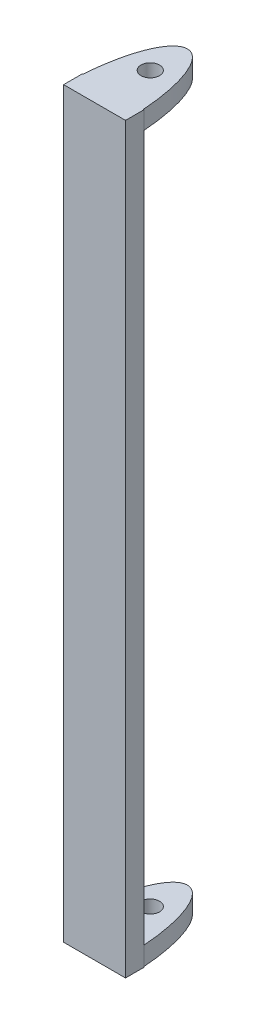
SolidWorks part; units mm, degrees
ref_plane "Front Plane" through (0, 0, 0) normal (0, 0, 1) x (1, 0, 0)
ref_plane "Top Plane" through (0, 0, 0) normal (0, 1, 0) x (1, 0, 0)
ref_plane "Right Plane" through (0, 0, 0) normal (1, 0, 0) x (0, 0, -1)
sketch "Sketch1" plane through (0, 0, 0) normal (0, 1, 0) x (1, 0, 0)
  line L1 (0, 0) -> (10, 0)
  ellipse E0 centre (5, 0) end of major axis (5, 15) minor radius 5 (10, 0) -> (0, 0) ccw
  dimension "D1" = 10
  dimension "D2" = 15
extrude "Boss-Extrude1" add sketch "Sketch1" along normal blind 3
sketch "Sketch2" plane through (0, 3, 0) normal (0, 1, 0) x (1, 0, 0)
  line L0 (0, 0) -> (10, 0) construction
  circle A0 centre (5, 9) radius 1.5
  point P4 (0, 0)
  point P5 (5, 0)
  dimension "D1" = 9
extrude "Cut-Extrude1" cut sketch "Sketch2" against normal through all
sketch "Sketch3" plane through (0, 0, 0) normal (0, 0, 1) x (1, 0, 0)
  line L1 (10, 3) -> (0, 3)
  line L2 (10, 3) -> (10, -117)
  line L3 (10, -117) -> (0, -117)
  line L4 (0, 3) -> (0, -117)
  dimension "D1" = 10
  dimension "D2" = 120
extrude "Boss-Extrude2" add sketch "Sketch3" against normal blind 3
ref_plane "Plane1" through (0, -57, 0) normal (0, 1, 0) x (1, 0, 0)
mirror "Mirror1" about plane through (0, -57, 0) normal (0, 1, 0) of "Cut-Extrude1", "Boss-Extrude1"
